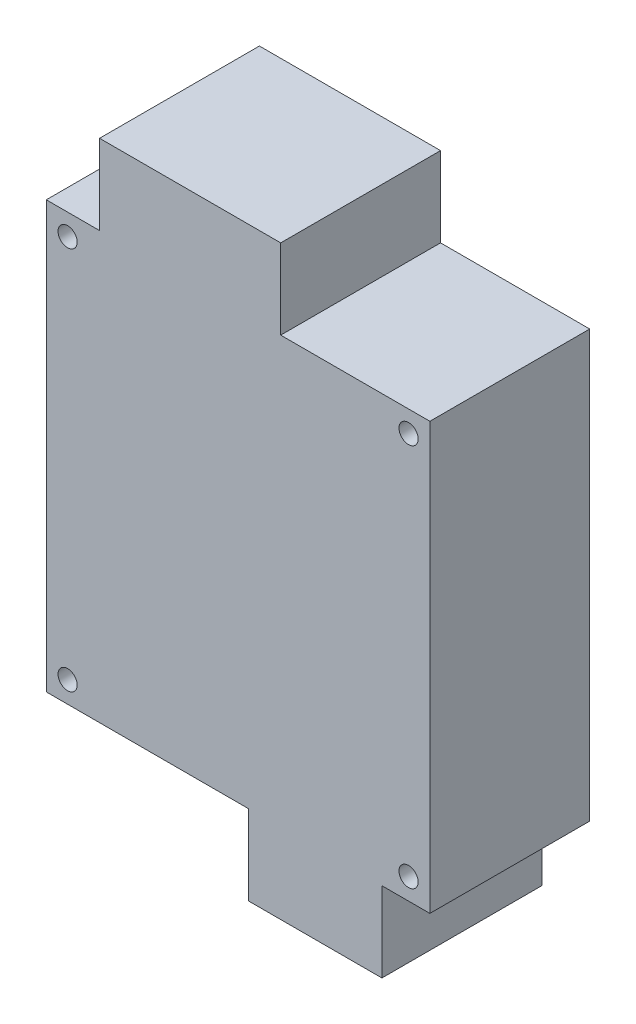
SolidWorks part; units mm, degrees
ref_plane "Plan de face" through (0, 0, 0) normal (0, 0, 1) x (1, 0, 0)
ref_plane "Plan de dessus" through (0, 0, 0) normal (0, 1, 0) x (1, 0, 0)
ref_plane "Plan de droite" through (0, 0, 0) normal (1, 0, 0) x (0, 0, -1)
sketch "Esquisse1" plane through (0, 0, 0) normal (0, 0, 1) x (1, 0, 0)
  line L1 (0, 0) -> (72, 0)
  line L2 (0, 0) -> (0, 110)
  line L3 (0, 110) -> (72, 110)
  line L4 (72, 0) -> (72, 110)
  dimension "D1" = 110
  dimension "D2" = 72
extrude "Boss.-Extru.1" add sketch "Esquisse1" along normal blind 30
sketch "Esquisse2" plane through (0, 0, 30) normal (0, 0, 1) x (1, 0, 0)
  line L0 (72, 110) -> (0, 110) construction
  line L4 (0, 110) -> (0, 0) construction
  circle A0 centre (4, 91) radius 1.5
  circle A1 centre (68, 91) radius 1.5
  circle A2 centre (4, 19) radius 1.5
  circle A3 centre (68, 19) radius 1.5
  dimension "D1" = 3
  dimension "D2" = 3
  dimension "D3" = 3
  dimension "D4" = 3
  dimension "D5" = 64
  dimension "D6" = 72
  dimension "D7" = 19
  dimension "D8" = 4
hole_wizard "Dégagement M31" positions "Esquisse3" profile "Esquisse4" hole size "M3" standard "ISO" end condition through all
sketch "Esquisse3" plane through (0, 0, 30) normal (0, 0, 1) x (1, 0, 0)
  point P0 (4, 91)
  point P3 (68, 91)
  point P6 (4, 19)
  point P9 (68, 19)
sketch "Esquisse4" plane through (4, 91, 30) normal (1, 0, 0) x (0, -1, 0)
  line L0 (0, 0) -> (0, 30)
  line L1 (0, 30) -> (1.8, 30)
  line L2 (1.8, 30) -> (1.8, 0)
  line L5 (1.8, 0) -> (0, 0)
  line L11 (0, -6.35) -> (0, 107.95) construction
  dimension "Diamètre du perçage jusqu'au prochain" = 3.6
  dimension "Profondeur du perçage jusqu'au prochain" = 30
sketch "Esquisse5" plane through (0, 0, 0) normal (0, 0, -1) x (-1, 0, 0)
  line L2 (0, 110) -> (-10, 110)
  line L3 (0, 110) -> (0, 95)
  line L4 (0, 95) -> (-10, 95)
  line L5 (-10, 110) -> (-10, 95)
  line L6 (0, 0) -> (-38, 0)
  line L7 (0, 0) -> (0, 15)
  line L8 (0, 15) -> (-38, 15)
  line L9 (-38, 0) -> (-38, 15)
  dimension "D1" = 15
  dimension "D2" = 10
  dimension "D3" = 38
  dimension "D4" = 15
extrude "Enlèv. mat.-Extru.1" cut sketch "Esquisse5" against normal up to surface (30 mm away) up to face at (5.8, 91, 30)
sketch "Esquisse6" plane through (0, 0, 0) normal (0, 0, -1) x (-1, 0, 0)
  line L1 (-72, 110) -> (-44, 110)
  line L2 (-72, 110) -> (-72, 95)
  line L3 (-72, 95) -> (-44, 95)
  line L4 (-44, 110) -> (-44, 95)
  line L5 (-72, 0) -> (-63, 0)
  line L6 (-72, 0) -> (-72, 15)
  line L7 (-72, 15) -> (-63, 15)
  line L8 (-63, 0) -> (-63, 15)
  dimension "D1" = 15
  dimension "D2" = 28
  dimension "D3" = 9
  dimension "D4" = 15
extrude "Enlèv. mat.-Extru.2" cut sketch "Esquisse6" against normal up to surface (30 mm away) up to face at (5.8, 91, 30)
